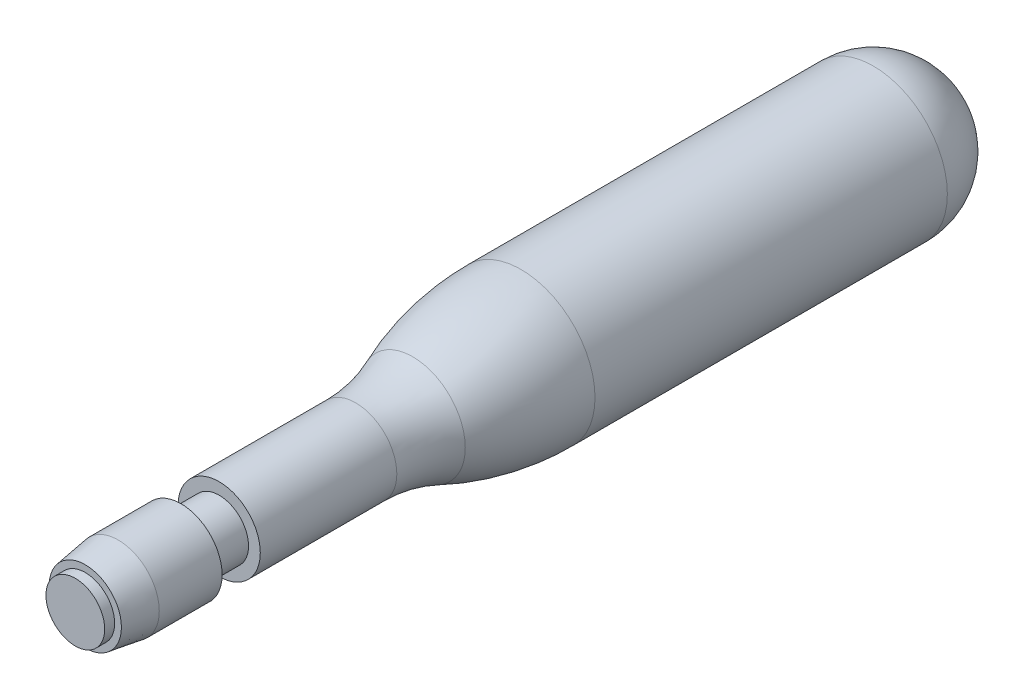
SolidWorks part; units mm, degrees
ref_plane "Front" through (0, 0, 0) normal (0, 0, 1) x (1, 0, 0)
ref_plane "Top" through (0, 0, 0) normal (0, 1, 0) x (1, 0, 0)
ref_plane "Right" through (0, 0, 0) normal (1, 0, 0) x (0, 0, -1)
sketch "Sketch1" plane through (0, 0, 0) normal (0, 1, 0) x (1, 0, 0)
  line L0 (0, 0) -> (0, 148.5)
  line L1 (12.6, 135.9) -> (12.6, 75.9)
  line L2 (7, 47.75) -> (7, 24.5)
  line L3 (7, 24.5) -> (5, 24.5)
  line L4 (5, 24.5) -> (5, 18)
  line L5 (5, 18) -> (7, 18)
  line L6 (7, 18) -> (7, 7.3)
  line L7 (7, 7.3) -> (6.15, 1.7)
  line L8 (6.15, 1.7) -> (5, 1.7)
  line L9 (5, 1.7) -> (5, 0)
  line L10 (5, 0) -> (0, 0)
  arc A0 (0, 148.5) -> (12.6, 135.9) centre (0, 135.9) cw
  arc A1 (12.6, 75.9) -> (8.9339, 57.4711) centre (-35.552, 75.9) cw
  arc A2 (8.9339, 57.4711) -> (7, 47.75) centre (32.4, 47.75) ccw
  point P11 (8.755, 56.5719)
  dimension "D13" = 25.4
  dimension "D1" = 148.5
  dimension "D2" = 12.6
  dimension "D3" = 7
  dimension "D4" = 60
  dimension "D5" = 23.25
  dimension "D6" = 5
  dimension "D7" = 1.7
  dimension "D8" = 5.6
  dimension "D9" = 6.15
  dimension "D10" = 7
  dimension "D11" = 16.3
  dimension "D12" = 6.5
revolve "Revolve1" add sketch "Sketch1" angle 360 about L0
